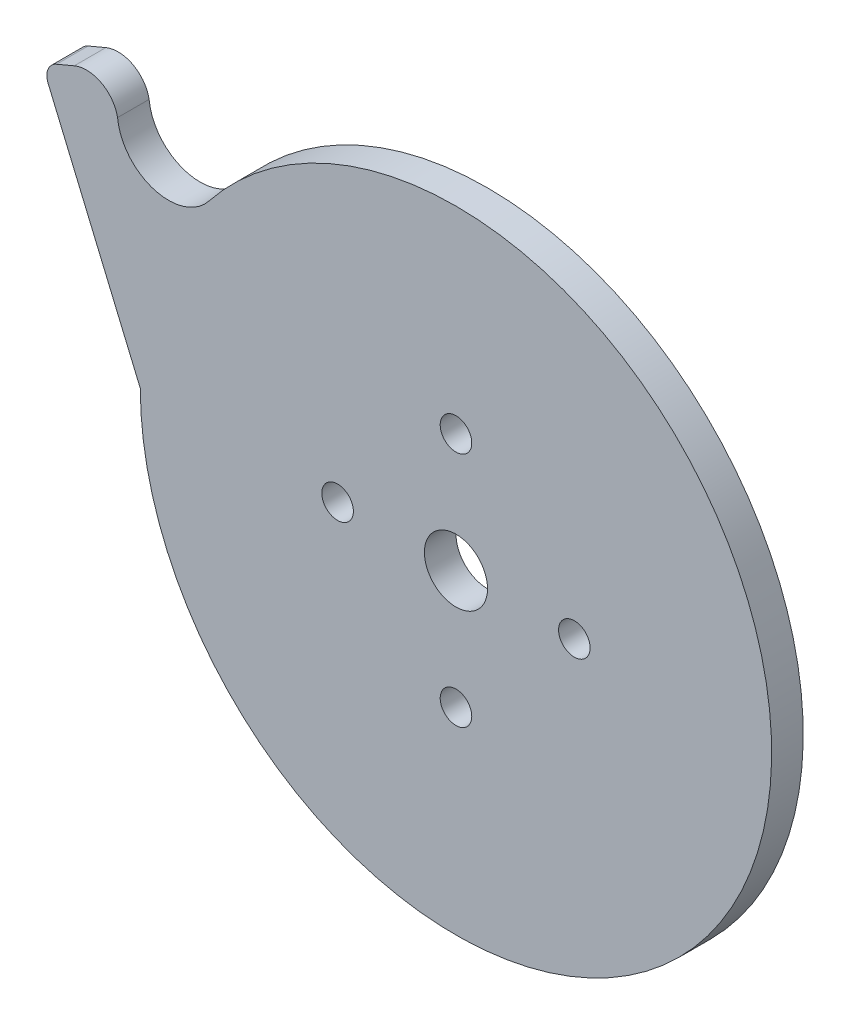
SolidWorks part; units mm, degrees
ref_plane "Front Plane" through (0, 0, 0) normal (0, 0, 1) x (1, 0, 0)
ref_plane "Top Plane" through (0, 0, 0) normal (0, 1, 0) x (1, 0, 0)
ref_plane "Right Plane" through (0, 0, 0) normal (1, 0, 0) x (0, 0, -1)
sketch "Sketch1" plane through (0, 0, 0) normal (0, 0, 1) x (1, 0, 0)
  line L0 (-40, 0) -> (-51.6812, 27.6324)
  line L1 (-50.6178, 30.2533) -> (-48.3674, 31.2046)
  arc A0 (-40, 0) -> (-31.3231, 24.877) centre (0, 0) ccw
  arc A1 (-48.3674, 31.2046) -> (-42.8802, 28.267) centre (-46.8099, 27.5203) cw
  arc A2 (-51.6812, 27.6324) -> (-50.6178, 30.2533) centre (-49.8391, 28.4111) cw
  arc A3 (-42.8802, 28.267) -> (-31.3231, 24.877) centre (-36.4131, 28.9195) ccw
  circle A4 centre (0, 0) radius 4
  circle A5 centre (0, 0) radius 15 construction
  circle A6 centre (0, 15) radius 2
  circle A7 centre (15, 0) radius 2
  circle A8 centre (0, -15) radius 2
  circle A9 centre (-15, 0) radius 2
  point P10 (-43.2492, 33.3683)
  point P13 (-52.46, 29.4746)
  point P26 (0, 0)
  dimension "D1" = 80
  dimension "D4" = 4
  dimension "D5" = 2
  dimension "D6" = 13
  dimension "D7" = 8
  dimension "D8" = 30
  dimension "D9" = 4
  dimension "D2" = 30
  dimension "D3" = 10
  dimension "D10" = 4
extrude "Boss-Extrude1" add sketch "Sketch1" along normal blind 4
